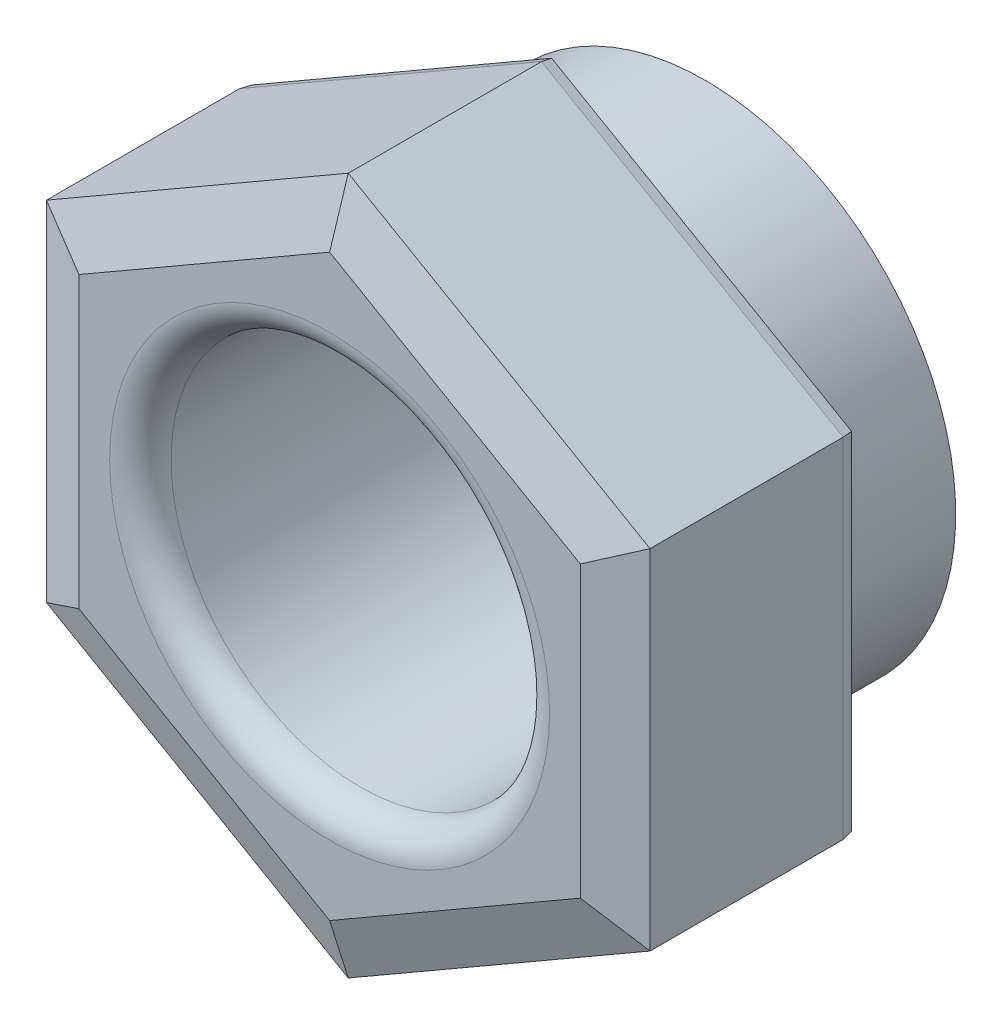
SolidWorks part; units mm, degrees
ref_plane "Plano frontal" through (0, 0, 0) normal (0, 0, 1) x (1, 0, 0)
ref_plane "Plano superior" through (0, 0, 0) normal (0, 1, 0) x (1, 0, 0)
ref_plane "Plano direito" through (0, 0, 0) normal (1, 0, 0) x (0, 0, -1)
sketch "Esboço1" plane through (0, 0, 0) normal (0, 0, 1) x (1, 0, 0)
  line L0 (0, -30.0229) -> (0, 50.9948) construction
  line L2 (0, -17.0318) -> (14.75, -8.5159)
  line L3 (14.75, -8.5159) -> (14.75, 8.5159)
  line L4 (14.75, 8.5159) -> (0, 17.0318)
  line L5 (0, 17.0318) -> (-14.75, 8.5159)
  line L6 (-14.75, 8.5159) -> (-14.75, -8.5159)
  line L7 (-14.75, -8.5159) -> (0, -17.0318)
  circle A0 centre (0, 0) radius 14.75 construction
  dimension "D1" = 29.5
extrude "Ressalto-extrusão1" add sketch "Esboço1" along normal blind 18.35
sketch "Esboço2" plane through (0, 0, 18.35) normal (0, 0, 1) x (1, 0, 0)
  line L0 (-14.75, 0) -> (14.75, 0) construction
  line L1 (-14.75, 8.5159) -> (-14.75, -8.5159) construction
  line L2 (14.75, -8.5159) -> (14.75, 8.5159) construction
  circle A0 centre (0, 0) radius 9.25
  dimension "D1" = 18.5
extrude "Corte-extrusão1" cut sketch "Esboço2" against normal through all
sketch "Esboço3" plane through (0, 0, 0) normal (0, 0, -1) x (-1, 0, 0)
  line L0 (-14.75, 0) -> (14.75, 0) construction
  line L1 (-14.75, -8.5159) -> (-14.75, 8.5159) construction
  line L2 (14.75, 8.5159) -> (14.75, -8.5159) construction
  circle A0 centre (0, 0) radius 12.25
  circle A1 centre (0, 0) radius 19.0975
  dimension "D1" = 24.5
extrude "Corte-extrusão2" cut sketch "Esboço3" against normal blind 7.5
fillet "Filete1" radius 2 1 edges at (9.25, 0, 0)
chamfer "Chanfro1" distance 0.5 angle 10 6 edges at (7.375, -12.7739, 7.5) (-7.375, -12.7739, 7.5) (-14.75, 0, 7.5) (-7.375, 12.7739, 7.5) (7.375, 12.7739, 7.5) (14.75, 0, 7.5)
fillet "Filete2" radius 1 1 edges at (-12.25, 0, 7.5)
chamfer "Chanfro3" distance 2.5 angle 20 6 edges at (-7.375, 12.7739, 18.35) (-14.75, 0, 18.35) (-7.375, -12.7739, 18.35) (7.375, -12.7739, 18.35) (7.375, 12.7739, 18.35) (14.75, 0, 18.35)
fillet "Filete3" radius 1.5 1 edges at (9.25, 0, 18.35)
